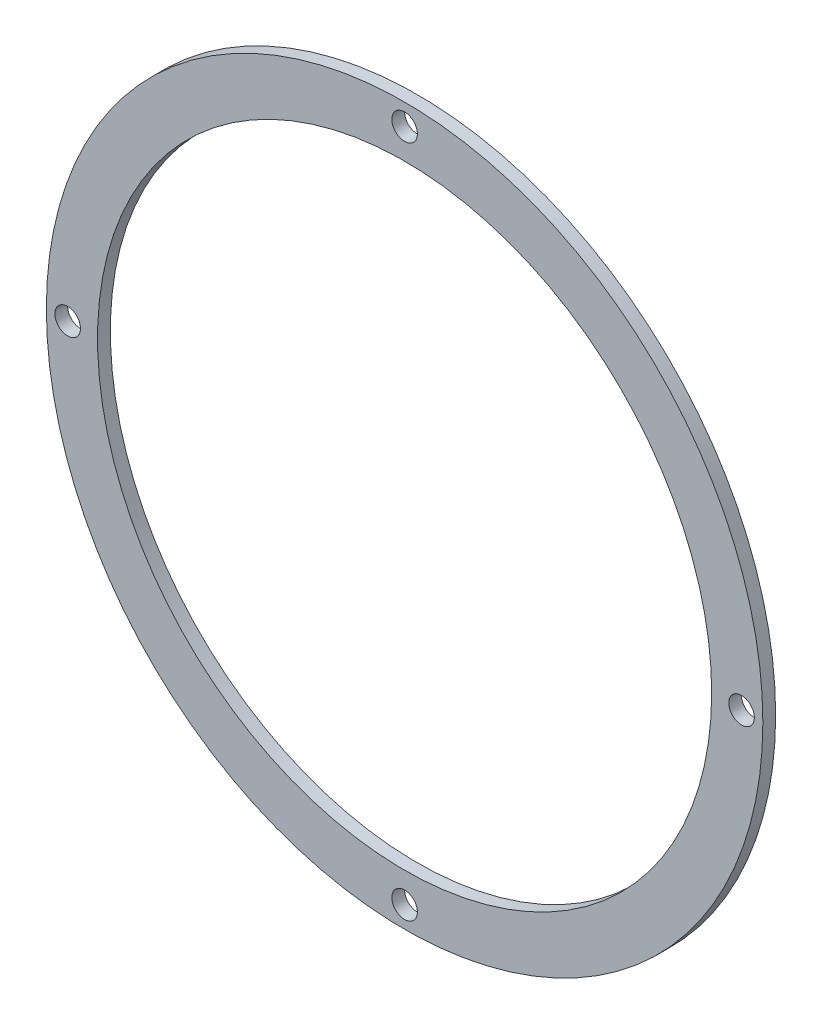
SolidWorks part; units mm, degrees
ref_plane "前视基准面" through (0, 0, 0) normal (0, 0, 1) x (1, 0, 0)
ref_plane "上视基准面" through (0, 0, 0) normal (0, 1, 0) x (1, 0, 0)
ref_plane "右视基准面" through (0, 0, 0) normal (1, 0, 0) x (0, 0, -1)
sketch "草图1" plane through (0, 0, 0) normal (0, 0, 1) x (1, 0, 0)
  circle A0 centre (0, 0) radius 72
  circle A1 centre (0, 0) radius 84
  circle A2 centre (0, 79) radius 3
  circle A3 centre (79, 0) radius 3
  circle A4 centre (0, -79) radius 3
  circle A5 centre (-79, 0) radius 3
  dimension "D1" = 144
  dimension "D2" = 168
  dimension "D4" = 6
  dimension "D3" = 79
  dimension "D5" = 4
extrude "凸台-拉伸1" add sketch "草图1" along normal blind 3
